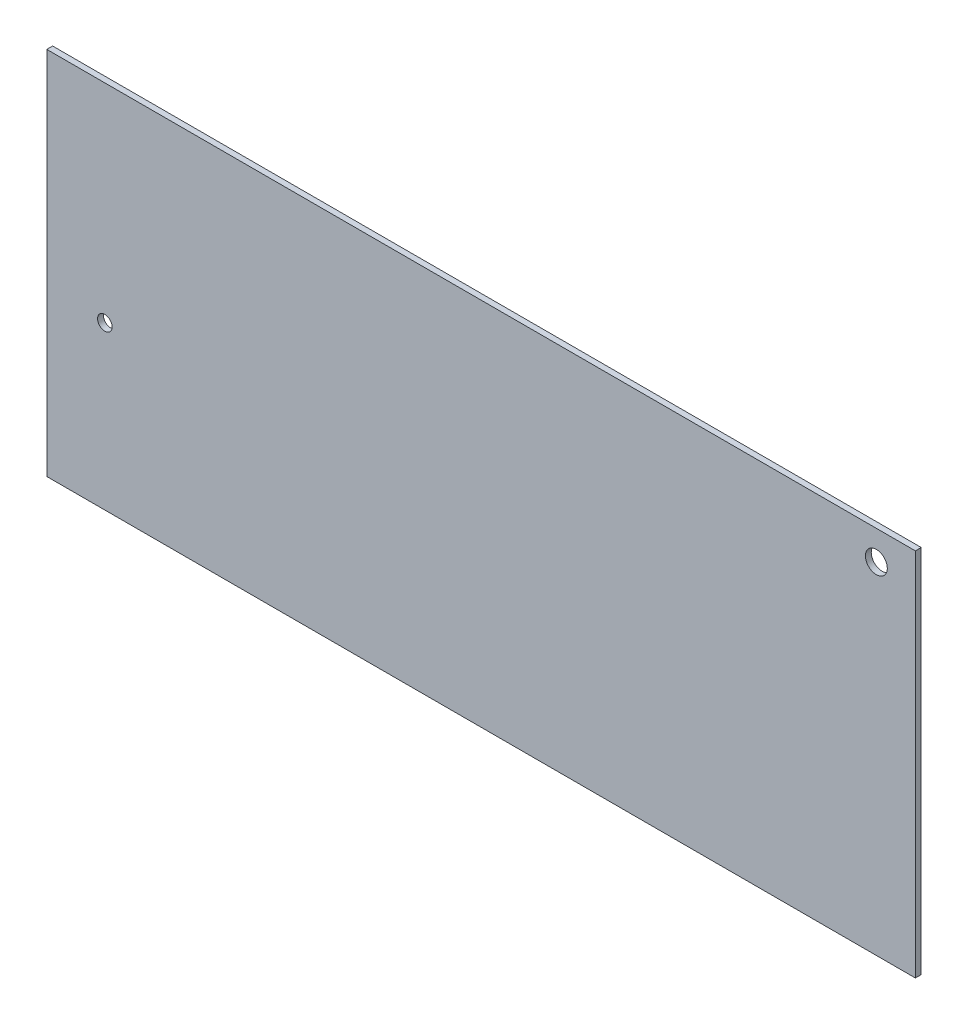
SolidWorks part; units mm, degrees
ref_plane "Front Plane" through (0, 0, 0) normal (0, 0, 1) x (1, 0, 0)
ref_plane "Top Plane" through (0, 0, 0) normal (0, 1, 0) x (1, 0, 0)
ref_plane "Right Plane" through (0, 0, 0) normal (1, 0, 0) x (0, 0, -1)
sketch "Sketch1" plane through (0, 0, 0) normal (0, 0, 1) x (1, 0, 0)
  line L1 (-255.9857, 41.9526) -> (121.8137, 41.9526)
  line L2 (-255.9857, 41.9526) -> (-255.9857, -118.9538)
  line L3 (-255.9857, -118.9538) -> (121.8137, -118.9538)
  line L4 (121.8137, 41.9526) -> (121.8137, -118.9538)
  point P0 (0, 0)
  point P5 (0, 0)
  point P6 (-227.8053, -118.9538)
  point P8 (0, 0)
  point P9 (121.8137, 41.9526)
extrude "Boss-Extrude1" add sketch "Sketch1" along normal blind 2.54
sketch "Sketch2" plane through (0, 0, 0) normal (0, 0, -1) x (-1, 0, 0)
  circle A1 centre (-104.844, 29.2526) radius 4.7625
extrude "Cut-Extrude1" cut sketch "Sketch2" against normal through all
sketch "Sketch3" plane through (0, 0, 0) normal (0, 0, -1) x (-1, 0, 0)
  circle A1 centre (230.7366, -48.435) radius 3.175
extrude "Cut-Extrude2" cut sketch "Sketch3" against normal through all
